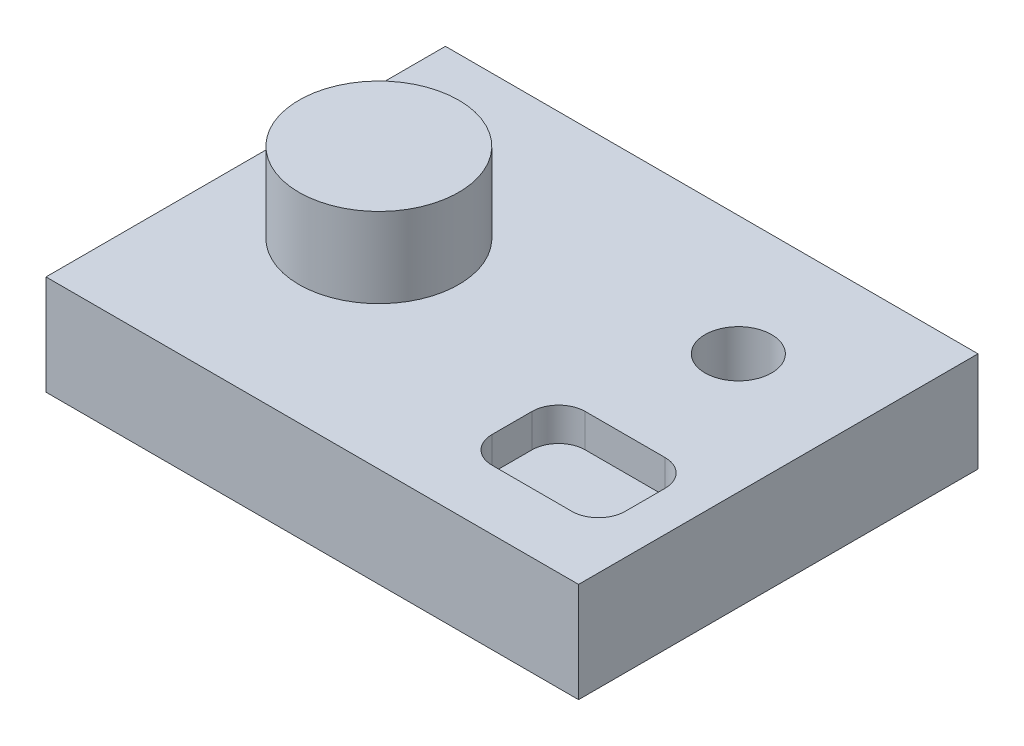
SolidWorks part; units mm, degrees
ref_plane "Front Plane" through (0, 0, 0) normal (0, 0, 1) x (1, 0, 0)
ref_plane "Top Plane" through (0, 0, 0) normal (0, 1, 0) x (1, 0, 0)
ref_plane "Right Plane" through (0, 0, 0) normal (1, 0, 0) x (0, 0, -1)
sketch "Sketch1" plane through (0, 0, 0) normal (0, 1, 0) x (1, 0, 0)
  line L1 (-40, -30) -> (40, -30)
  line L2 (-40, -30) -> (-40, 30)
  line L3 (-40, 30) -> (40, 30)
  line L4 (40, -30) -> (40, 30)
extrude "Boss-Extrude1" add sketch "Sketch1" along normal blind 15
sketch "Sketch2" plane through (0, 15, 0) normal (0, 1, 0) x (1, 0, 0)
  circle A0 centre (-20, 0) radius 12
extrude "Boss-Extrude2" add sketch "Sketch2" along normal blind 12
sketch "Sketch3" plane through (0, 15, 0) normal (0, 1, 0) x (1, 0, 0)
  circle A0 centre (22, 12) radius 5
extrude "Cut-Extrude2" cut sketch "Sketch3" against normal blind 10
sketch "Sketch4" plane through (0, 15, 0) normal (0, 1, 0) x (1, 0, 0)
  line L0 (18, -21) -> (30, -21)
  line L1 (34, -17) -> (34, -11)
  line L2 (30, -7) -> (18, -7)
  line L3 (14, -11) -> (14, -17)
  arc A0 (30, -21) -> (34, -17) centre (30, -17) ccw
  arc A1 (34, -11) -> (30, -7) centre (30, -11) ccw
  arc A2 (18, -7) -> (14, -11) centre (18, -11) ccw
  arc A3 (14, -17) -> (18, -21) centre (18, -17) ccw
extrude "Cut-Extrude4" cut sketch "Sketch4" against normal blind 5
